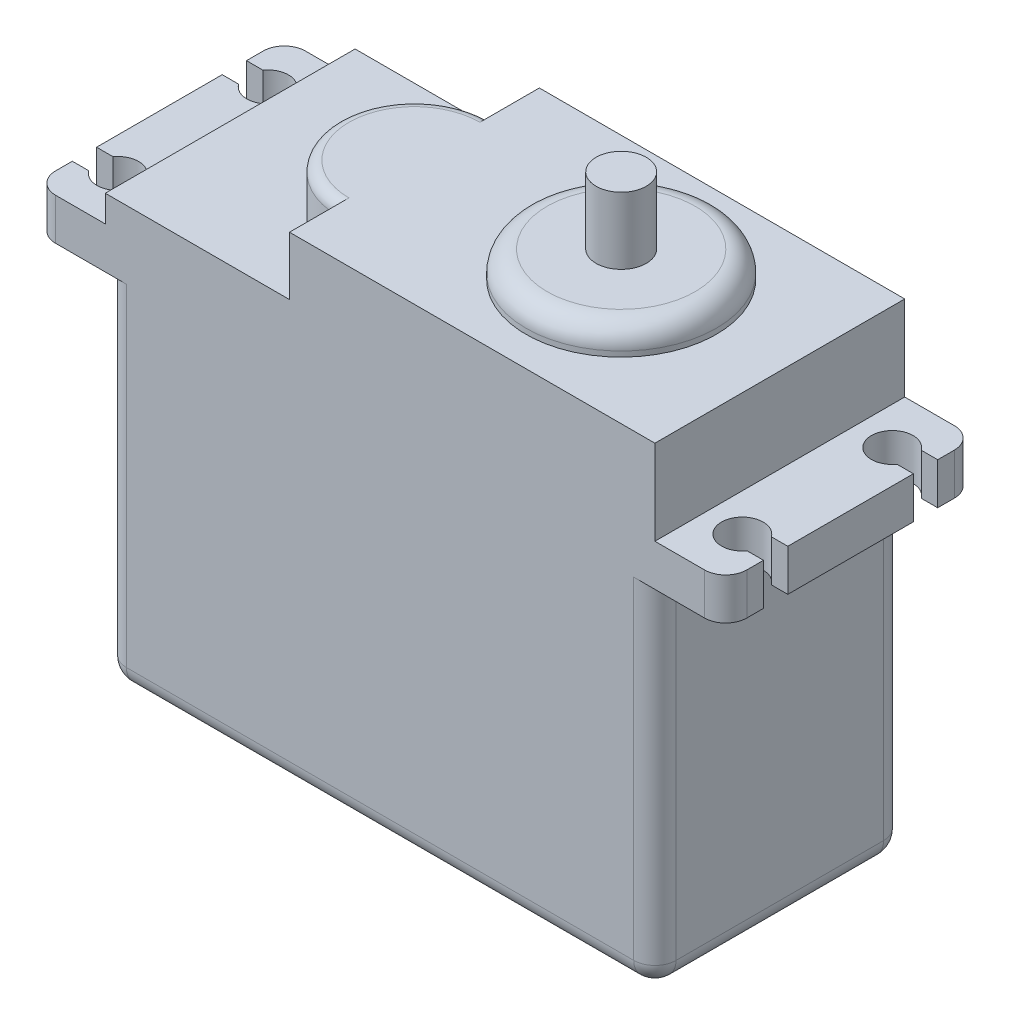
SolidWorks part; units mm, degrees
material "PE Low/Medium Density"
ref_plane "Front Plane" through (0, 0, 0) normal (0, 0, 1) x (1, 0, 0)
ref_plane "Top Plane" through (0, 0, 0) normal (0, 1, 0) x (1, 0, 0)
ref_plane "Right Plane" through (0, 0, 0) normal (1, 0, 0) x (0, 0, -1)
sketch "Sketch1" plane through (0, 0, 0) normal (0, 0, 1) x (1, 0, 0)
  line L0 (0, 25.2975) -> (0, -25.2975) construction
  line L1 (-33, 17.1025) -> (-41.5, 17.1025)
  line L2 (-33, 17.1025) -> (-33, -25.2975)
  line L3 (-33, -25.2975) -> (33, -25.2975)
  line L4 (33, 17.1025) -> (33, -25.2975)
  line L5 (-41.5, 17.1025) -> (-41.5, 22.1025)
  line L6 (-41.5, 22.1025) -> (-33, 22.1025)
  line L7 (-33, 22.1025) -> (-33, 25.2975)
  line L8 (-33, 25.2975) -> (-10.8777, 25.2975)
  line L9 (-10.8777, 25.2975) -> (-10.8777, 32.3025)
  line L10 (-10.8777, 32.3025) -> (33, 32.3025)
  line L11 (33, 17.1025) -> (41.5, 17.1025)
  line L12 (41.5, 17.1025) -> (41.5, 22.1025)
  line L13 (41.5, 22.1025) -> (33, 22.1025)
  line L14 (33, 22.1025) -> (33, 32.3025)
  dimension "D1" = 66
  dimension "D2" = 42.4
  dimension "D3" = 83
  dimension "D4" = 57.6
  dimension "D5" = 5
extrude "Extrude1" add sketch "Sketch1" along normal blind 30
fillet "Fillet1" radius 2.54 12 edges at (-33, -25.2975, 15) (0, -25.2975, 30) (33, -25.2975, 15) (0, -25.2975, 0) (41.5, 19.6025, 30) (41.5, 19.6025, 0) (33, -4.0975, 0) (33, -4.0975, 30) (-33, -4.0975, 30) (-33, -4.0975, 0) (-41.5, 19.6025, 0) (-41.5, 19.6025, 30)
sketch "Sketch2" plane through (0, 22.1025, 0) normal (0, 1, 0) x (1, 0, 0)
  line L0 (-37.5, -24) -> (-37.5, -6) construction
  line L1 (-41.5, -15) -> (41.5, -15) construction
  line L2 (-41.5, -27.46) -> (-41.5, -2.54) construction
  line L3 (41.5, -27.46) -> (41.5, -2.54) construction
  line L4 (37.5, -6) -> (37.5, -24) construction
  circle A0 centre (-37.5, -6) radius 2.5
  circle A1 centre (-37.5, -24) radius 2.5
  circle A2 centre (37.5, -6) radius 2.5
  circle A3 centre (37.5, -24) radius 2.5
  dimension "D2" = 5
  dimension "D1" = 18
  dimension "D3" = 4
  dimension "D4" = 4
extrude "Cut-Extrude1" cut sketch "Sketch2" against normal up to next
sketch "Sketch3" plane through (0, 22.1025, 0) normal (0, 1, 0) x (1, 0, 0)
  line L0 (-41.5, -15) -> (41.5, -15) construction
  line L1 (-41.5, -27.46) -> (-41.5, -2.54) construction
  line L2 (41.5, -27.46) -> (41.5, -2.54) construction
  line L3 (-40, -6) -> (40, -6) construction
  line L4 (40, -24) -> (-40, -24) construction
  line L6 (-37.551, -7.4579) -> (-41.5, -7.4579)
  line L7 (-37.551, -7.4579) -> (-37.551, -4.5421)
  line L8 (-37.551, -4.5421) -> (-41.5, -4.5421)
  line L9 (-41.5, -7.4579) -> (-41.5, -4.5421)
  line L10 (-37.551, -25.4579) -> (-41.5, -25.4579)
  line L11 (-37.551, -25.4579) -> (-37.551, -22.5421)
  line L12 (-37.551, -22.5421) -> (-41.5, -22.5421)
  line L13 (-41.5, -25.4579) -> (-41.5, -22.5421)
  line L14 (36.24, -4.5421) -> (41.5, -4.5421)
  line L15 (36.24, -4.5421) -> (36.24, -7.4579)
  line L16 (36.24, -7.4579) -> (41.5, -7.4579)
  line L17 (41.5, -4.5421) -> (41.5, -7.4579)
  line L18 (36.9891, -22.5421) -> (41.5, -22.5421)
  line L19 (36.9891, -22.5421) -> (36.9891, -25.4579)
  line L20 (36.9891, -25.4579) -> (41.5, -25.4579)
  line L21 (41.5, -22.5421) -> (41.5, -25.4579)
  circle A0 centre (-37.5, -6) radius 2.5 construction
  circle A1 centre (37.5, -6) radius 2.5 construction
  circle A2 centre (37.5, -24) radius 2.5 construction
  circle A3 centre (-37.5, -24) radius 2.5 construction
extrude "Cut-Extrude2" cut sketch "Sketch3" against normal up to next
sketch "Sketch4" plane through (0, 25.2975, 0) normal (0, 1, 0) x (1, 0, 0)
  line L0 (-10.8777, -30) -> (-10.8777, 0) construction
  line L1 (-10.8777, -5.8698) -> (-10.8777, -24.1302)
  arc A0 (-10.8777, -5.8698) -> (-10.8777, -24.1302) centre (-10.8777, -15) ccw
extrude "Extrude2" add sketch "Sketch4" along normal up to surface (7.0049 mm away) up to face at (11.0612, 32.3025, 15)
sketch "Sketch5" plane through (0, 32.3025, 0) normal (0, 1, 0) x (1, 0, 0)
  line L0 (33, -15) -> (-41.5, -15) construction
  line L1 (33, -30) -> (33, 0) construction
  line L2 (-41.5, -22.5421) -> (-41.5, -7.4579) construction
  circle A0 centre (13.95, -15) radius 11.43
  dimension "D1" = 22.86
  dimension "D2" = 19.05
extrude "Extrude3" add sketch "Sketch5" along normal blind 3.175
fillet "Fillet2" radius 2.54 1 edges at (13.95, 35.4775, 26.43)
fillet "Fillet3" radius 1.27 1 edges at (-20.0079, 32.3025, 15)
sketch "Sketch6" plane through (0, 35.4775, 0) normal (0, 1, 0) x (1, 0, 0)
  circle A0 centre (13.95, -15) radius 3.013
extrude "Extrude4" add sketch "Sketch6" along normal offset from surface (8.025 mm away) 68.8 up to face at (0, -25.2975, 15)
